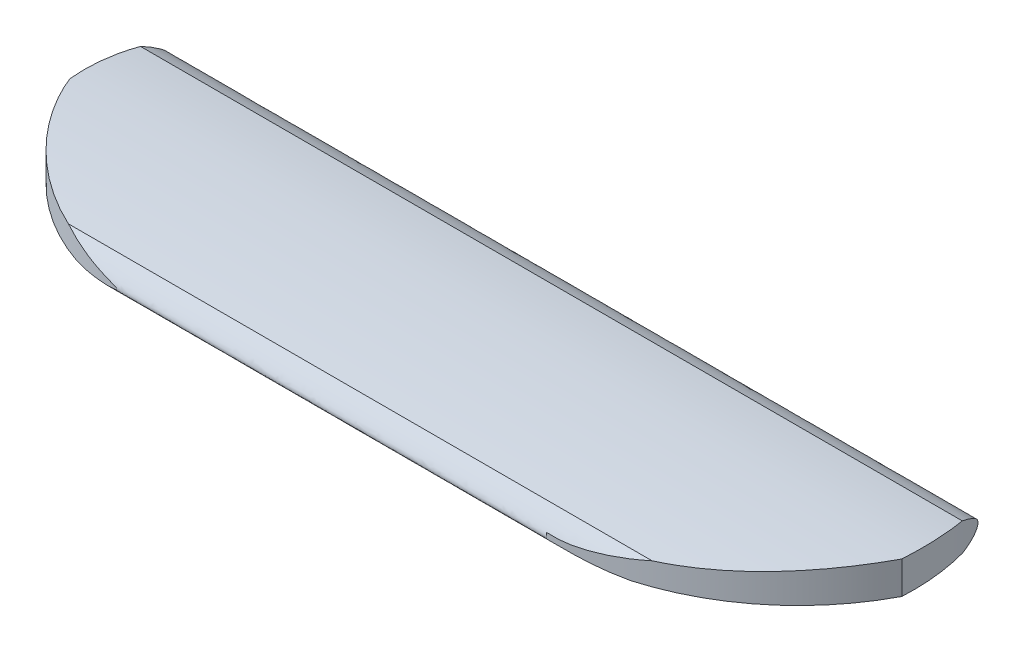
SolidWorks part; units mm, degrees
ref_plane "Front Plane" through (0, 0, 0) normal (0, 0, 1) x (1, 0, 0)
ref_plane "Top Plane" through (0, 0, 0) normal (0, 1, 0) x (1, 0, 0)
ref_plane "Right Plane" through (0, 0, 0) normal (1, 0, 0) x (0, 0, -1)
sketch "Sketch1" plane through (0, 0, 0) normal (0, 1, 0) x (1, 0, 0)
  line L1 (-125, 35) -> (125, 35)
  line L2 (-125, 35) -> (-125, -35)
  line L3 (-125, -35) -> (125, -35)
  line L4 (125, 35) -> (125, -35)
  line L5 (-125, 35) -> (125, -35) construction
  line L6 (-125, -35) -> (125, 35) construction
  point P0 (0, 0)
  dimension "D1" = 250
  dimension "D2" = 70
extrude "Boss-Extrude1" add sketch "Sketch1" along normal blind 10
sketch "Sketch2" plane through (0, 10, 0) normal (0, 1, 0) x (1, 0, 0)
  line L0 (-125, -35) -> (125, -35) construction
  arc A1 (-113.7569, 49.4108) -> (-102.5852, -37.9855) centre (-57.1436, 12.2354) ccw
  arc A2 (-113.7569, 49.4108) -> (-141.9395, 79.6977) centre (-150.767, 43.2278) ccw
  arc A3 (-141.9395, 79.6977) -> (-154.9504, 8.8084) centre (-140.3895, 42.7746) ccw
  arc A4 (-154.9504, 8.8084) -> (-129.2993, -65.688) centre (-142.1249, -28.4398) ccw
  arc A5 (-129.2993, -65.688) -> (-105.6812, -35) centre (-117.4902, -50.344) ccw
  line M2 (125, 35) -> (-125, 35)
  line M3 (-125, 35) -> (-125, -35)
  line M4 (-125, -35) -> (125, -35)
extrude "Cut-Extrude1" cut sketch "Sketch2" against normal blind 10 contours A1 M2 M3 M4 | A4 A5 A1 A2 A3 M4 M3 M2
sketch "Sketch3" plane through (0, 10, 0) normal (0, 1, 0) x (1, 0, 0)
  arc A0 (107.6709, -35.2928) -> (119.1574, 35.1422) centre (60.4026, 8.5698) ccw
  arc A1 (119.1574, 35.1422) -> (153.4275, 45.7783) centre (141.6105, 23.3252) cw
  arc A2 (153.4275, 45.7783) -> (168.6246, 1.1272) centre (195.7668, 35.2769) cw
  arc A3 (168.6246, 1.1272) -> (107.6709, -35.2928) centre (131.261, -5.5569) cw
extrude "Cut-Extrude2" cut sketch "Sketch3" against normal blind 10
sketch "Sketch7" plane through (0, 0, 0) normal (1, 0, 0) x (0, 0, -1)
  arc A0 (33.5334, 7.2922) -> (-36.2988, 5.5012) centre (3.3244, -177.1288) ccw
  arc A1 (33.5334, 7.2922) -> (63.0952, 54.3099) centre (72.7236, 15.4541) ccw
  arc A2 (63.0952, 54.3099) -> (-38.9637, 82.8623) centre (12.0658, 68.5861) ccw
  arc A3 (-38.9637, 82.8623) -> (-75.1028, 29.6213) centre (-66.0927, 62.3913) ccw
  arc A4 (-75.1028, 29.6213) -> (-36.2988, 5.5012) centre (-36.2604, 48.8364) ccw
extrude "Cut-Extrude7" cut sketch "Sketch7" along normal through all both and the other way through all
sketch "Sketch8" plane through (0, 0, 0) normal (1, 0, 0) x (0, 0, -1)
  line L0 (-28.0666, 7.9602) -> (-42.7099, 11.8603)
  line L1 (-42.7099, 11.8603) -> (-42.7099, -7.9931)
  line L2 (-42.7099, -7.9931) -> (-28.7119, -0.4666)
  spline S0 degree 3 poles (-28.0666, 7.9602) (-39.5981, 0.5139) (-33.2204, 0.3708) (-28.7119, -0.4666) knots 0 0 0 0 0.838508 0.838508 0.838508 0.838508
extrude "Cut-Extrude12" cut sketch "Sketch8" against normal through all both and the other way through all
sketch "Sketch9" plane through (0, 0, 0) normal (0, -1, 0) x (-1, 0, 0)
  line L0 (124.6559, 5.4847) -> (146.364, -21.0026)
  line L2 (66.4238, -43.3789) -> (70.7882, -34.5718)
  line L3 (146.364, -21.0026) -> (76.2108, -48.2289)
  line L4 (76.2108, -48.2289) -> (66.4238, -43.3789)
  arc A0 (70.7882, -34.5718) -> (124.6559, 5.4847) centre (65.2525, 29.1214) ccw
extrude "Cut-Extrude15" cut sketch "Sketch9" against normal blind 10
sketch "Sketch10" plane through (0, 0, 0) normal (0, -1, 0) x (-1, 0, 0)
  line L0 (-57.6752, -34.2754) -> (-71.5438, -47.2005)
  line L1 (-71.5438, -47.2005) -> (-140.9078, -43.3264)
  line L2 (-140.9078, -43.3264) -> (-154.2665, 14.8386)
  line L3 (-154.2665, 14.8386) -> (-126.8629, 9.383)
  arc A0 (-126.8629, 9.383) -> (-57.6752, -34.2754) centre (-59.6099, 39.3103) ccw
extrude "Cut-Extrude16" cut sketch "Sketch10" against normal blind 10
sketch "Sketch11" plane through (0, 0, 0) normal (1, 0, 0) x (0, 0, -1)
  line L0 (25.2308, 8.5001) -> (41.0257, 16.1864)
  line L1 (41.0257, 16.1864) -> (42.5575, 1.8779)
  line L2 (42.5575, 1.8779) -> (37.2109, -12.4791)
  line L3 (37.2109, -12.4791) -> (27.145, -6.2294)
  line L4 (27.145, -6.2294) -> (24.5392, -0.1675)
  spline S0 degree 2 poles (25.2308, 8.5001) (39.968, 2.1529) (24.5392, -0.1675) knots 0 0 0 1 1 1
  point P2 (25.1419, 8.0886)
  point P8 (32.5446, 3.2332)
  point P9 (24.5392, -0.1675)
  point P10 (32.4091, 3.0292)
  point P11 (25.1469, 8.1395)
  point P12 (25.2, 8.3757)
  point P13 (25.2308, 8.5001)
extrude "Cut-Extrude21" cut sketch "Sketch11" against normal through all both and the other way through all
